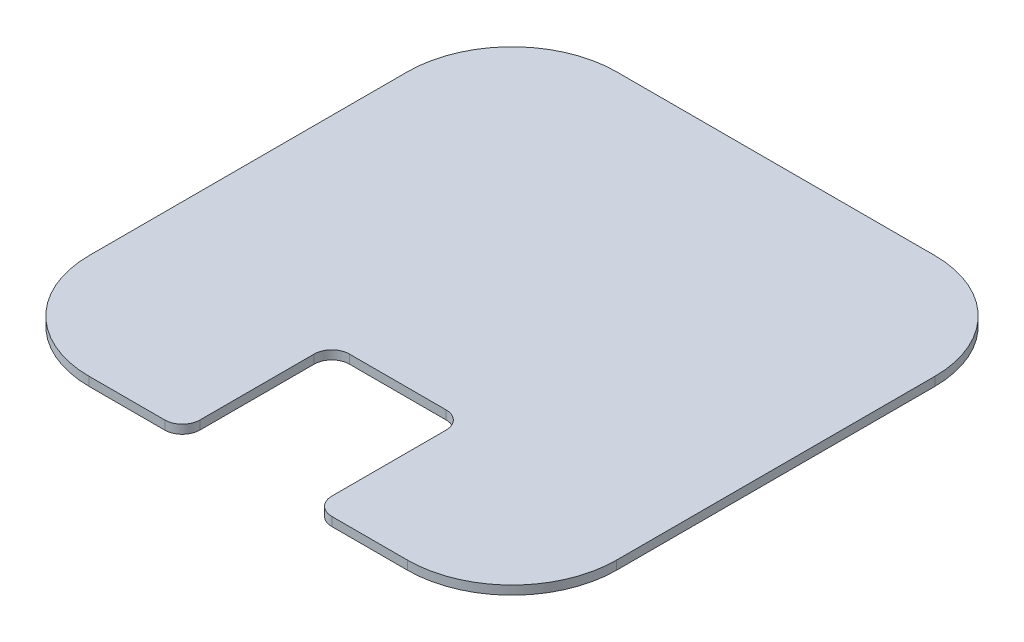
SolidWorks part; units mm, degrees
ref_plane "Front Plane" through (0, 0, 0) normal (0, 0, 1) x (1, 0, 0)
ref_plane "Top Plane" through (0, 0, 0) normal (0, 1, 0) x (1, 0, 0)
ref_plane "Right Plane" through (0, 0, 0) normal (1, 0, 0) x (0, 0, -1)
sketch "Sketch2" plane through (0, 0, 0) normal (0, 1, 0) x (1, 0, 0)
  line L1 (-18.1066, -30) -> (18.1066, -30)
  line L2 (-30, -18.1066) -> (-30, 18.1066)
  line L3 (-18.1066, 30) -> (18.1066, 30)
  line L4 (30, -18.1066) -> (30, 18.1066)
  line L5 (-30, -30) -> (30, 30) construction
  line L6 (-30, 30) -> (30, -30) construction
  arc A0 (18.1066, 30) -> (30, 18.1066) centre (18.1066, 18.1066) cw
  arc A1 (30, -18.1066) -> (18.1066, -30) centre (18.1066, -18.1066) cw
  arc A2 (-18.1066, -30) -> (-30, -18.1066) centre (-18.1066, -18.1066) cw
  arc A3 (-30, 18.1066) -> (-18.1066, 30) centre (-18.1066, 18.1066) cw
  point P0 (0, 0)
  point P18 (-26.5165, 26.5165)
  point P19 (26.5165, -26.5165)
  dimension "D1" = 60
  dimension "D2" = 60
  dimension "D3" = 75
extrude "Boss-Extrude1" add sketch "Sketch2" along normal blind 1
sketch "Sketch3" plane through (0, 0, 0) normal (0, 1, 0) x (1, 0, 0)
  line L0 (-18.1066, -30) -> (18.1066, -30) construction
  line L1 (-7.5, -30) -> (7.5, -30)
  line L2 (-7.5, -30) -> (-7.5, -13)
  line L3 (-7.5, -13) -> (7.5, -13)
  line L4 (7.5, -30) -> (7.5, -13)
  point P6 (0, -13)
  dimension "D1" = 15
  dimension "D2" = 17
extrude "Cut-Extrude1" cut sketch "Sketch3" along normal blind 1
fillet "Fillet1" radius 2 4 edges at (7.5, 0.5, 30) (-7.5, 0.5, 30) (7.5, 0.5, 13) (-7.5, 0.5, 13)
